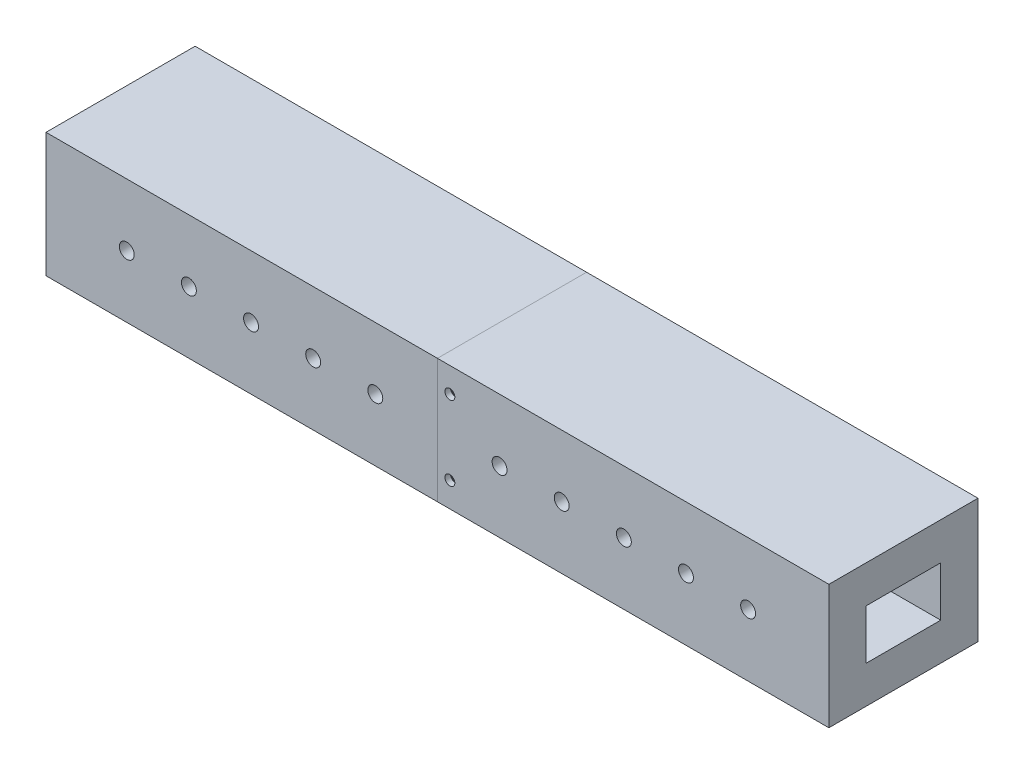
SolidWorks part; units mm, degrees
ref_plane "Front Plane" through (0, 0, 0) normal (0, 0, 1) x (1, 0, 0)
ref_plane "Top Plane" through (0, 0, 0) normal (0, 1, 0) x (1, 0, 0)
ref_plane "Right Plane" through (0, 0, 0) normal (1, 0, 0) x (0, 0, -1)
sketch "Sketch1" plane through (0, 0, 0) normal (0, 1, 0) x (1, 0, 0)
  line L1 (-157.5, 30) -> (157.5, 30)
  line L2 (-157.5, 30) -> (-157.5, -30)
  line L3 (-157.5, -30) -> (157.5, -30)
  line L4 (157.5, 30) -> (157.5, -30)
  line L5 (-157.5, 30) -> (157.5, -30) construction
  line L6 (-157.5, -30) -> (157.5, 30) construction
  point P0 (0, 0)
  dimension "31.5" = 315
  dimension "D2" = 60
extrude "Boss-Extrude1" add sketch "Sketch1" along normal blind 50
sketch "Sketch2" plane through (-157.5, 0, 0) normal (-1, 0, 0) x (0, 0, 1)
  line L10 (-30, 50) -> (-30, 0) construction
  line L11 (-15, 35) -> (15, 35)
  line L12 (-15, 35) -> (-15, 15)
  line L13 (-15, 15) -> (15, 15)
  line L14 (15, 35) -> (15, 15)
  line L15 (-15, 35) -> (15, 15) construction
  line L16 (-15, 15) -> (15, 35) construction
  line L17 (30, 50) -> (30, 0) construction
  line L18 (-30, 0) -> (30, 0) construction
  line L19 (-30, 50) -> (30, 50) construction
  point P0 (0, 25)
  dimension "D1" = 15
  dimension "D2" = 15
  dimension "D3" = 15
  dimension "D4" = 15
extrude "Cut-Extrude1" cut sketch "Sketch2" against normal through all
sketch "Sketch3" plane through (0, 0, 30) normal (0, 0, 1) x (1, 0, 0)
  line L0 (0, 0) -> (0, 114.6137) construction
  line L1 (-157.5, 25) -> (157.5, 25) construction
  line L2 (-157.5, 50) -> (-157.5, 0) construction
  line L3 (157.5, 50) -> (157.5, 0) construction
  circle A0 centre (-25, 25) radius 3
  circle A1 centre (-50, 25) radius 3
  circle A2 centre (-75, 25) radius 3
  circle A3 centre (-100, 25) radius 3
  circle A4 centre (-125, 25) radius 3
  circle A5 centre (125, 25) radius 3
  circle A6 centre (100, 25) radius 3
  circle A7 centre (75, 25) radius 3
  circle A8 centre (50, 25) radius 3
  circle A9 centre (25, 25) radius 3
  dimension "D1" = 6
  dimension "D2" = 25
  dimension "D3" = 5
extrude "Cut-Extrude2" cut sketch "Sketch3" against normal blind 10
split "Split1" trim tools "Right Plane" bodies to split 103 resulting bodies 104 105
sketch "Sketch4" plane through (0, 0, 0) normal (-1, 0, 0) x (0, 0, 1)
  line L0 (30, 50) -> (30, 0) construction
  line L1 (17.25, 47.75) -> (27.75, 47.75)
  line L2 (17.25, 47.75) -> (17.25, 2.25)
  line L3 (17.25, 2.25) -> (27.75, 2.25)
  line L4 (27.75, 47.75) -> (27.75, 2.25)
  line L5 (17.25, 47.75) -> (27.75, 2.25) construction
  line L6 (17.25, 2.25) -> (27.75, 47.75) construction
  line L7 (0, 25) -> (55.0174, 25) construction
  line L8 (0, -27.5) -> (0, 27.5) construction
  line L9 (-17.25, 2.25) -> (-27.75, 2.25)
  line L10 (-27.75, 47.75) -> (-27.75, 2.25)
  line L11 (-17.25, 47.75) -> (-27.75, 47.75)
  line L12 (-17.25, 47.75) -> (-17.25, 2.25)
  line L13 (0, 0) -> (0, 69.6324) construction
  line L14 (30, 0) -> (-30, 0) construction
  point P0 (22.5, 25)
  dimension "D1" = 7.5
  dimension "D2" = 10.5
  dimension "D3" = 45.5
  dimension "D4" = 25
extrude "Cut-Extrude3" cut sketch "Sketch4" against normal blind 10
sketch "Sketch5" plane through (0, 0, 30) normal (0, 0, 1) x (1, 0, 0)
  line L0 (0, 50) -> (0, 0) construction
  line L1 (0, 25) -> (-24.9807, 25) construction
  circle A0 centre (5, 40) radius 2
  circle A1 centre (5, 10) radius 2
  dimension "D1" = 4
  dimension "D2" = 5
  dimension "D3" = 30
extrude "Cut-Extrude4" cut sketch "Sketch5" against normal blind 10
mirror "Mirror1" about plane through (0, 0, 0) normal (0, 0, 1) of "Cut-Extrude4"
sketch "Sketch6" plane through (0, 0, 0) normal (1, 0, 0) x (0, 0, -1)
  line L0 (-30, 50) -> (-30, 0) construction
  line L1 (-27.5, 47.5) -> (-17.5, 47.5)
  line L2 (-27.5, 47.5) -> (-27.5, 2.5)
  line L3 (-27.5, 2.5) -> (-17.5, 2.5)
  line L4 (-17.5, 47.5) -> (-17.5, 2.5)
  line L5 (-27.5, 47.5) -> (-17.5, 2.5) construction
  line L6 (-27.5, 2.5) -> (-17.5, 47.5) construction
  line L7 (-30, 0) -> (30, 0) construction
  line L8 (0, 27.5) -> (0, -27.5) construction
  line L9 (27.5, 2.5) -> (17.5, 47.5) construction
  line L10 (27.5, 47.5) -> (17.5, 2.5) construction
  line L11 (17.5, 47.5) -> (17.5, 2.5)
  line L12 (27.5, 2.5) -> (17.5, 2.5)
  line L13 (27.5, 47.5) -> (27.5, 2.5)
  line L14 (27.5, 47.5) -> (17.5, 47.5)
  point P0 (-22.5, 25)
  point P15 (22.5, 25)
  dimension "D1" = 10
  dimension "D2" = 45
  dimension "D3" = 7.5
  dimension "D4" = 2.5
extrude "Boss-Extrude2" add sketch "Sketch6" along normal blind 10
sketch "Sketch8" plane through (0, 0, 27.5) normal (0, 0, 1) x (1, 0, 0)
  line L0 (10, 47.5) -> (10, 2.5) construction
  line L1 (10, 25) -> (33.2597, 25) construction
  circle A0 centre (5, 40) radius 2
  circle A1 centre (5, 10) radius 2
  dimension "D1" = 4
  dimension "D2" = 5
  dimension "D3" = 30
extrude "Cut-Extrude6" cut sketch "Sketch8" against normal through all
sketch "Sketch9" plane through (0, 0, 0) normal (0, -1, 0) x (1, 0, 0)
  line L0 (157.5, 30) -> (157.5, -30) construction
  line L1 (-157.5, 0) -> (271.778, 0) construction
  line L2 (-157.5, -30) -> (-157.5, 30) construction
  line L3 (0, 30) -> (0, -30) construction
  circle A0 centre (137.5, 15) radius 2
  circle A1 centre (137.5, -15) radius 2
  circle A2 centre (-137.5, -15) radius 2
  circle A3 centre (-137.5, 15) radius 2
  dimension "D1" = 4
  dimension "D2" = 20
  dimension "D3" = 30
extrude "Cut-Extrude7" cut sketch "Sketch9" against normal blind 10
sketch "Sketch10" plane through (0, 0, -30) normal (0, 0, -1) x (-1, 0, 0)
  line L0 (0, 0) -> (0, 83.7486) construction
  line L1 (0, 25) -> (95.066, 25) construction
  line L2 (0, 0) -> (157.5, 0) construction
  circle A0 centre (30, 40) radius 2
  circle A1 centre (30, 10) radius 2
  circle A2 centre (-30, 10) radius 2
  circle A3 centre (-30, 40) radius 2
  dimension "D2" = 4
  dimension "D1" = 25
  dimension "D3" = 30
  dimension "D4" = 30
extrude "Cut-Extrude8" cut sketch "Sketch10" against normal blind 10
other "Save Bodies1"
